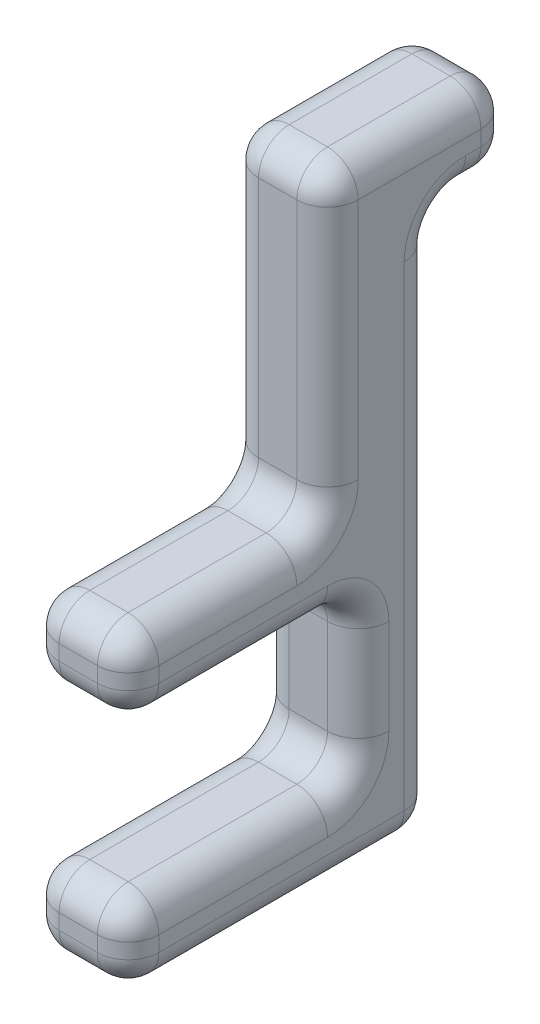
SolidWorks part; units mm, degrees
ref_plane "Front Plane" through (0, 0, 0) normal (0, 0, 1) x (1, 0, 0)
ref_plane "Top Plane" through (0, 0, 0) normal (0, 1, 0) x (1, 0, 0)
ref_plane "Right Plane" through (0, 0, 0) normal (1, 0, 0) x (0, 0, -1)
sketch "Sketch1" plane through (0, 0, 0) normal (0, 0, 1) x (1, 0, 0)
  line L1 (0, 0) -> (-6.5, 0)
  line L2 (0, 0) -> (0, 40)
  line L3 (0, 40) -> (-6.5, 40)
  line L4 (-6.5, 0) -> (-6.5, 40)
  dimension "D1" = 40
  dimension "D2" = 6.5
extrude "Boss-Extrude1" add sketch "Sketch1" along normal blind 20
sketch "Sketch2" plane through (0, 0, 0) normal (1, 0, 0) x (0, 0, -1)
  line L0 (-20, 0) -> (-20, 40) construction
  line L1 (-20, 15.2) -> (-5, 15.2)
  line L2 (-20, 15.2) -> (-20, 5)
  line L3 (-20, 5) -> (-5, 5)
  line L4 (-5, 15.2) -> (-5, 5)
  line L5 (-20, 0) -> (0, 0) construction
  line L6 (0, 0) -> (0, 40) construction
  dimension "10,5" = 10.2
  dimension "D1" = 5
  dimension "D2" = 5
extrude "Cut-Extrude1" cut sketch "Sketch2" against normal through all
fillet "Fillet1" radius 2 8 edges at (-6.5, 5, 12.5) (0, 5, 12.5) (-6.5, 15.2, 12.5) (0, 15.2, 12.5) (-3.25, 5, 5) (-6.5, 10.1, 5) (-3.25, 15.2, 5) (0, 10.1, 5)
sketch "Sketch4" plane through (-6.5, 0, 0) normal (-1, 0, 0) x (0, 0, 1)
  line L1 (20, 20.2) -> (7, 20.2)
  line L2 (20, 20.2) -> (20, 40)
  line L3 (20, 40) -> (7, 40)
  line L4 (7, 20.2) -> (7, 40)
  line L12 (20, 15.2) -> (7, 15.2) construction
  dimension "D1" = 5
extrude "Cut-Extrude3" cut sketch "Sketch4" against normal through all
sketch "Sketch6" plane through (0, 0, 0) normal (0, 0, -1) x (-1, 0, 0)
  line L1 (0, 40) -> (6.5, 40)
  line L2 (0, 40) -> (0, 35)
  line L3 (0, 35) -> (6.5, 35)
  line L4 (6.5, 40) -> (6.5, 35)
  dimension "D1" = 5
extrude "Boss-Extrude2" add sketch "Sketch6" along normal blind 5
fillet "Fillet2" radius 2 32 edges at (-3.25, 35, -5) (-3.25, 40, -5) (-6.5, 35, -2.5) (-6.5, 37.5, -5) (-6.5, 40, 1) (-6.5, 17.5, 0) (-3.25, 35, 0) (-6.5, 0, 10) (-3.25, 0, 0) (-0.5858, 4.4142, 20) (-3.25, 0, 20) (-6.5, 1.5, 20) (-5.9142, 4.4142, 20) (-3.25, 5, 20) (-0.5858, 15.7858, 20) (-3.25, 15.2, 20) (-5.9142, 15.7858, 20) (-6.5, 18.7, 20) (-3.25, 20.2, 20) (-6.5, 20.2, 13.5) (-3.25, 40, 7) (-3.25, 20.2, 7) (-6.5, 30.1, 7) (0, 40, 1) (0, 37.5, -5) (0, 35, -2.5) (0, 17.5, 0) (0, 0, 10) (0, 1.5, 20) (0, 18.7, 20) (0, 20.2, 13.5) (0, 30.1, 7)
equation "\"A\"= 10.2mm"
equation "\"10,5@Sketch2\" = \"A\""
